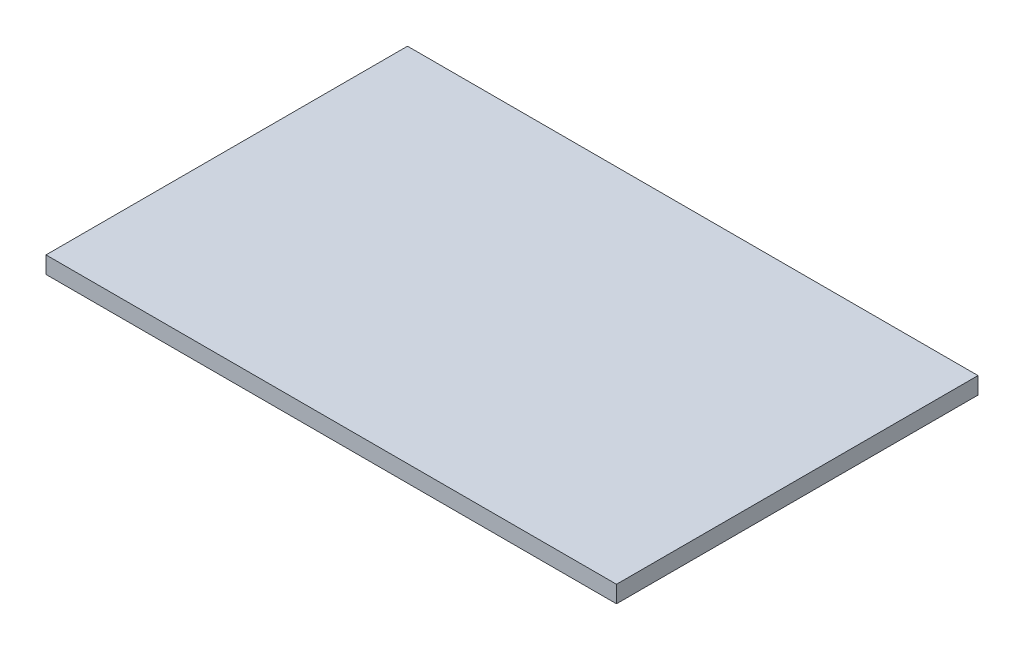
SolidWorks part; units mm, degrees
ref_plane "Front Plane" through (0, 0, 0) normal (0, 0, 1) x (1, 0, 0)
ref_plane "Top Plane" through (0, 0, 0) normal (0, 1, 0) x (1, 0, 0)
ref_plane "Right Plane" through (0, 0, 0) normal (1, 0, 0) x (0, 0, -1)
sketch "Sketch1" plane through (0, 0, 0) normal (0, 1, 0) x (1, 0, 0)
  line L1 (-50.5, -32) -> (50.5, -32)
  line L2 (-50.5, -32) -> (-50.5, 32)
  line L3 (-50.5, 32) -> (50.5, 32)
  line L4 (50.5, -32) -> (50.5, 32)
  line L5 (-50.5, -32) -> (50.5, 32) construction
  line L6 (-50.5, 32) -> (50.5, -32) construction
  point P0 (0, 0)
  dimension "D1" = 101
  dimension "D2" = 64
extrude "Boss-Extrude1" add sketch "Sketch1" along normal blind 3
